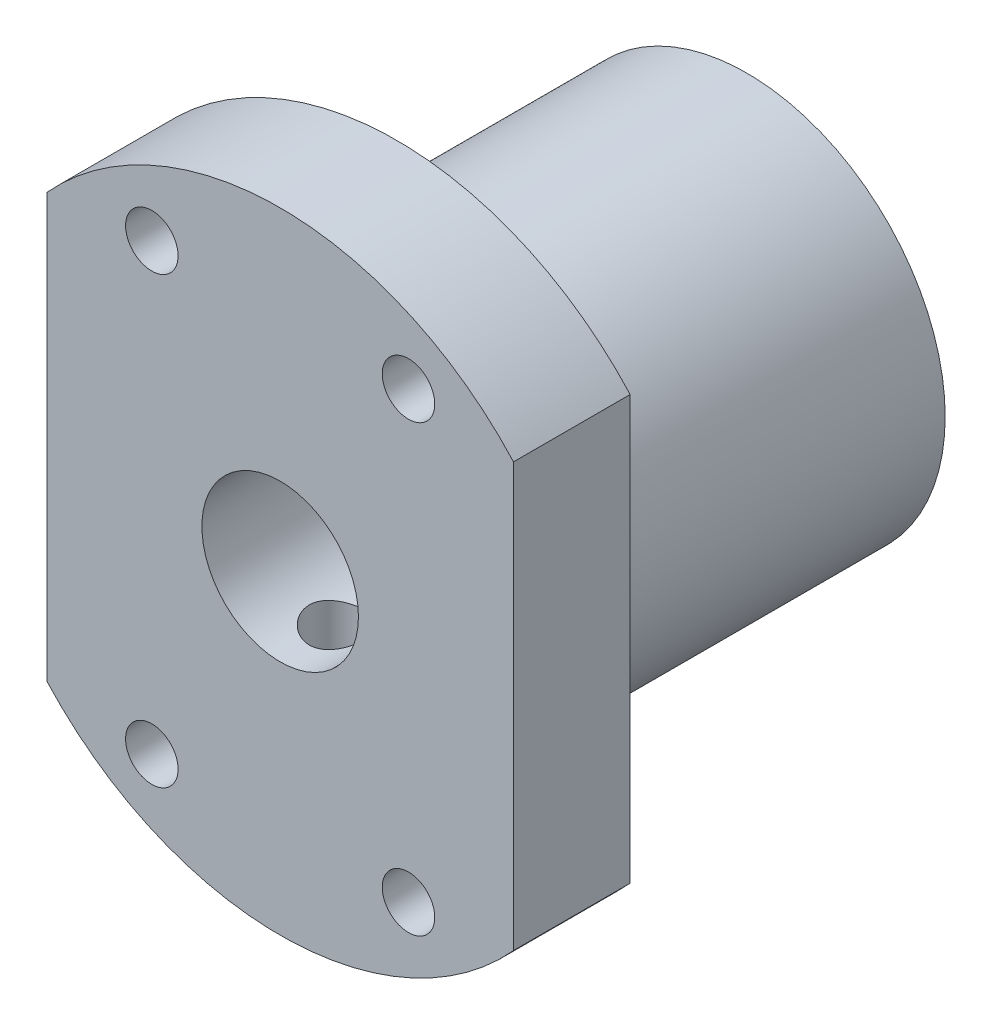
SolidWorks part; units mm, degrees
ref_plane "Plano frontal" through (0, 0, 0) normal (0, 0, 1) x (1, 0, 0)
ref_plane "Plano superior" through (0, 0, 0) normal (0, 1, 0) x (1, 0, 0)
ref_plane "Plano direito" through (0, 0, 0) normal (1, 0, 0) x (0, 0, -1)
sketch "Sketch1" plane through (0, 0, 0) normal (0, 0, 1) x (1, 0, 0)
  circle A0 centre (0, 0) radius 17
  dimension "D1" = 34
extrude "Boss-Extrude1" add sketch "Sketch1" along normal blind 30
sketch "Sketch3" plane through (0, 0, 30) normal (0, 0, 1) x (1, 0, 0)
  line L0 (0, 0) -> (0, 17) construction
  line L1 (0, 0) -> (17, 0) construction
  line L2 (0, 0) -> (15.6149, 27.0457) construction
  line L3 (0, 0) -> (-15.6149, 27.0457) construction
  line L4 (-20, -18.1384) -> (-20, 18.1384)
  line L5 (20, -18.1384) -> (20, 18.1384)
  circle A0 centre (0, 0) radius 17 construction
  arc A2 (-20, -9.1652) -> (20, -9.1652) centre (0, 0) ccw construction
  arc A3 (-20, -18.1384) -> (20, -18.1384) centre (0, 0) ccw
  arc A5 (20, 18.1384) -> (-20, 18.1384) centre (0, 0) ccw
  arc A6 (20, 9.1652) -> (-20, 9.1652) centre (0, 0) ccw construction
  dimension "D1" = 44
  dimension "D2" = 54
  dimension "D3" = 30
  dimension "D5" = 20
extrude "Boss-Extrude2" add sketch "Sketch3" along normal blind 10
sketch "Sketch4" plane through (0, 0, 40) normal (0, 0, 1) x (1, 0, 0)
  circle A0 centre (0, 0) radius 6.71
  dimension "D1" = 13.42
extrude "Cut-Extrude1" cut sketch "Sketch4" against normal through all contours A0
cosmetic thread "Cosmetic Thread1" parameters "D2"=16
ref_plane "Plane1" through (0, -27, 0) normal (0, -1, 0) x (-1, 0, 0)
hole_wizard "Tap Drill for M6x1.0 Tap1" positions "Sketch12" profile "Sketch13" hole size "M6x1.0" standard "Ansi Metric"
sketch "Sketch12" plane through (0, -27, 0) normal (0, -1, 0) x (-1, 0, 0)
  line L0 (-20, -40) -> (-20, -30) construction
  line L1 (20, -30) -> (-20, -30) construction
  point P0 (0, -35)
  dimension "D1" = 20
  dimension "D2" = 5
sketch "Sketch13" plane through (0, -27, 35) normal (1, 0, 0) x (0, 0, -1)
  line L0 (0, 0) -> (0, 20.29)
  line L1 (0, 20.29) -> (2.5, 20.29)
  line L2 (2.5, 20.29) -> (2.5, 0)
  line L5 (2.5, 0) -> (0, 0)
  line L11 (0, -6.35) -> (0, 107.95) construction
  dimension "Thru Hole Dia." = 5
  dimension "Thru Hole Depth" = 20.29
cosmetic thread "Cosmetic Thread2" parameters "D1"=8, "D2"=6
hole_wizard "Ø4.5 (4.5) Diameter Hole1" positions "Sketch14" profile "Sketch16" hole size "Ø4.5" standard "ISO"
sketch "Sketch14" plane through (0, 0, 40) normal (0, 0, 1) x (1, 0, 0)
  line L0 (0, 0.4094) -> (0, -49999.5906) construction
  line L1 (0, 0) -> (13.5, 23.3827) construction
  line L3 (0, 0) -> (-13.5, 23.3827) construction
  arc A0 (20, 18.1384) -> (-20, 18.1384) centre (0, 0) ccw construction
  circle A1 centre (0, 0) radius 22 construction
  point P34 (-11, 19.0526)
  point P70 (11, 19.0526)
  point P71 (22, 0) [skipped]
  point P72 (11, -19.0526)
  point P73 (-11, -19.0526)
  point P74 (-22, 0) [skipped]
  dimension "D3" = 44
  dimension "D1" = 30
  dimension "D2" = 30
  dimension "D4" = 6
sketch "Sketch16" plane through (-11, -19.0526, 40) normal (1, 0, 0) x (0, -1, 0)
  line L0 (0, 0) -> (0, 40)
  line L1 (0, 40) -> (2.25, 40)
  line L2 (2.25, 40) -> (2.25, 0)
  line L5 (2.25, 0) -> (0, 0)
  line L11 (0, -6.35) -> (0, 107.95) construction
  dimension "Thru Hole Dia." = 4.5
  dimension "Thru Hole Depth" = 40
